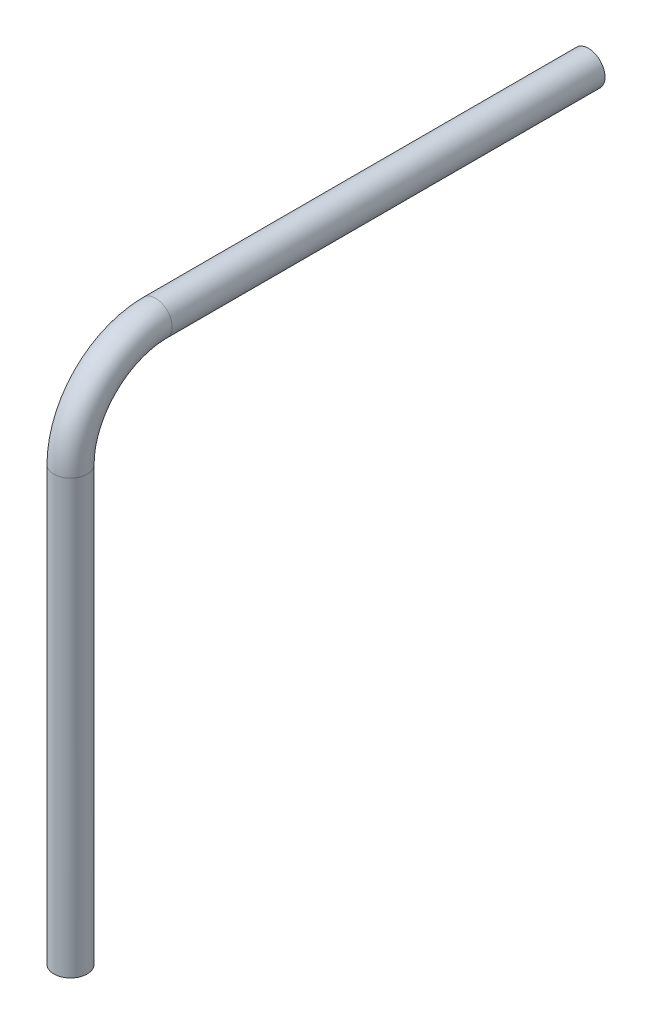
SolidWorks part; units mm, degrees
material "Cast Carbon Steel"
ref_plane "Front Plane" through (0, 0, 0) normal (0, 0, 1) x (1, 0, 0)
ref_plane "Top Plane" through (0, 0, 0) normal (0, 1, 0) x (1, 0, 0)
ref_plane "Right Plane" through (0, 0, 0) normal (1, 0, 0) x (0, 0, -1)
sketch "Sketch2" plane through (0, 0, 0) normal (1, 0, 0) x (0, 0, -1)
  arc A0 (-64.8338, 0) -> (0, 64.8338) centre (0, 0) cw
sketch "Sketch3" plane through (0, 0, 0) normal (0, 1, 0) x (1, 0, 0)
  circle A0 centre (0, -64.8338) radius 12.7
  dimension "D1" = 25.4
sweep "Sweep1" add profiles "Sketch3" path "Sketch2"
ref_plane "Plane1" through (0, 0, 0) normal (0, -1, 0) x (-1, 0, 0)
ref_plane "Plane2" through (0, 0, 0) normal (0, 0, -1) x (-1, 0, 0)
sketch "Sketch4" plane through (0, 0, 0) normal (0, -1, 0) x (-1, 0, 0)
  circle A0 centre (0, -64.8338) radius 12.7
extrude "Boss-Extrude3" add sketch "Sketch4" along normal blind 330.2
sketch "Sketch5" plane through (0, 0, 0) normal (0, 0, -1) x (-1, 0, 0)
  circle A0 centre (0, 64.8338) radius 12.7
extrude "Boss-Extrude4" add sketch "Sketch5" along normal blind 330.2
ref_plane "Plane3" through (-12.7, 0, 0) normal (-1, 0, 0) x (0, 0, 1)
sketch "Sketch6" plane through (-12.7, 0, 0) normal (-1, 0, 0) x (0, 0, 1)
  line L0 (52.1338, 0) -> (77.5338, 0) construction
  line L1 (57.15, -152.4) -> (69.85, -152.4)
  line L2 (57.15, -152.4) -> (57.15, 0)
  line L3 (57.15, 0) -> (69.85, 0)
  line L4 (69.85, -152.4) -> (69.85, 0)
  point P6 (52.5037, -330.2)
  point P12 (63.5, -152.4)
  point P13 (63.5, -152.4)
  point P15 (0, 0)
  dimension "D1" = 57.15
  dimension "D2" = 63.5
  dimension "D3" = 152.4
extrude "Cut-Extrude1" cut sketch "Sketch6" against normal blind 6.35
